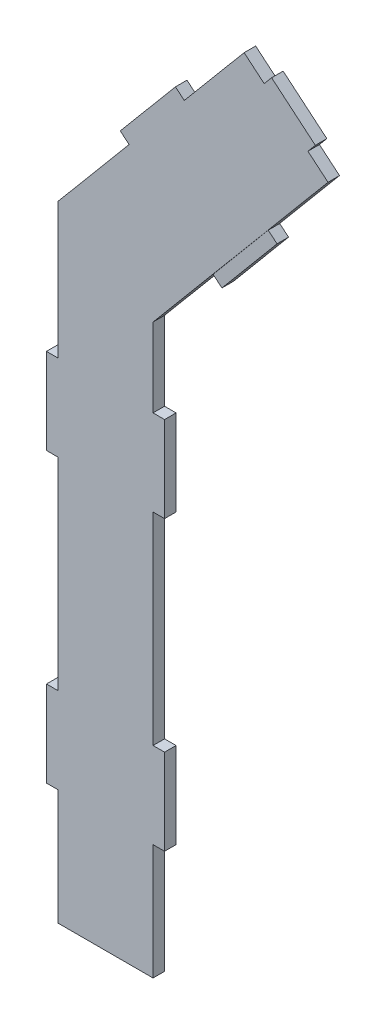
SolidWorks part; units mm, degrees
ref_plane "Front Plane" through (0, 0, 0) normal (0, 0, 1) x (1, 0, 0)
ref_plane "Top Plane" through (0, 0, 0) normal (0, 1, 0) x (1, 0, 0)
ref_plane "Right Plane" through (0, 0, 0) normal (1, 0, 0) x (0, 0, -1)
sketch "Sketch1" plane through (0, 0, 0) normal (0, 0, 1) x (1, 0, 0)
  line L0 (16.5, 98.61) -> (46.8717, 134.8056)
  line L1 (0, 0) -> (16.5, 0)
  line L2 (0, 0) -> (0, 20.05)
  line L4 (16.5, 0) -> (16.5, 98.61)
  line L5 (0, 108.5) -> (12.3446, 123.2117)
  line L6 (32.3129, 147.0091) -> (35.7976, 144.0882)
  line L7 (8.25, 0) -> (8.25, 118.332) construction
  line L8 (40.8759, 142.4411) -> (8.25, 103.5182) construction
  line L10 (0, 20.05) -> (-2, 20.05)
  line L12 (0, 34.95) -> (-2, 34.95)
  line L13 (-2, 20.05) -> (-2, 34.95)
  line L14 (0, 70.05) -> (-2, 70.05)
  line L16 (0, 84.95) -> (-2, 84.95)
  line L17 (-2, 70.05) -> (-2, 84.95)
  line L18 (12.3446, 123.2117) -> (10.8125, 124.4973)
  line L19 (21.9222, 134.6258) -> (20.3901, 135.9114)
  line L20 (10.8125, 124.4973) -> (20.3901, 135.9114)
  line L22 (35.7976, 144.0882) -> (37.0824, 145.6209)
  line L23 (43.3847, 137.7285) -> (44.6695, 139.2612)
  line L24 (37.0824, 145.6209) -> (44.6695, 139.2612)
  line L25 (0, 84.95) -> (0, 108.5)
  line L26 (0, 34.95) -> (0, 70.05)
  line L27 (21.9222, 134.6258) -> (32.3129, 147.0091)
  line L28 (43.3847, 137.7285) -> (46.8717, 134.8056)
  line L29 (31.6859, 116.7078) -> (15.6013, 130.2043) construction
  line L30 (18.5, 70.05) -> (18.5, 84.95)
  line L31 (16.5, 84.95) -> (18.5, 84.95)
  line L32 (16.5, 70.05) -> (18.5, 70.05)
  line L33 (18.5, 20.05) -> (18.5, 34.95)
  line L34 (16.5, 34.95) -> (18.5, 34.95)
  line L35 (16.5, 20.05) -> (18.5, 20.05)
  line L40 (16.5, 84.95) -> (16.5, 70.05)
  line L41 (16.5, 34.95) -> (16.5, 20.05)
  line L42 (26.9256, 110.9897) -> (28.459, 109.7057)
  line L43 (28.459, 109.7057) -> (38.0248, 121.1296)
  line L44 (36.4914, 122.4136) -> (38.0248, 121.1296)
  line L45 (36.4914, 122.4136) -> (26.9256, 110.9897)
  point P26 (-2, 27.5)
  point P29 (-2, 77.5)
  point P37 (40.8759, 142.4411)
  dimension "D1" = 16.5
  dimension "D2" = 98.61
  dimension "D3" = 108.5
  dimension "D4" = 140
  dimension "D5" = 47.25
  dimension "D6" = 50.27
  dimension "D7" = 14.9
  dimension "D8" = 9.9
  dimension "D9" = 2
  dimension "D10" = 27.5
  dimension "D11" = 50
  dimension "D12" = 2
  dimension "D13" = 2
  dimension "D14" = 18.9969
  dimension "D15" = 4.55
  dimension "D16" = 4.5469
extrude "Boss-Extrude2" add sketch "Sketch1" along normal blind 2 contours L28 L23 L24 L22 L6 L27 L19 L20 L18 L5 L25 L16 L17 L14 L26 L12 L13 L10 L2 L1 L4 L0 | L4 L32 L30 L31 | L4 L35 L33 L34 | L44 L45 L42 L43
